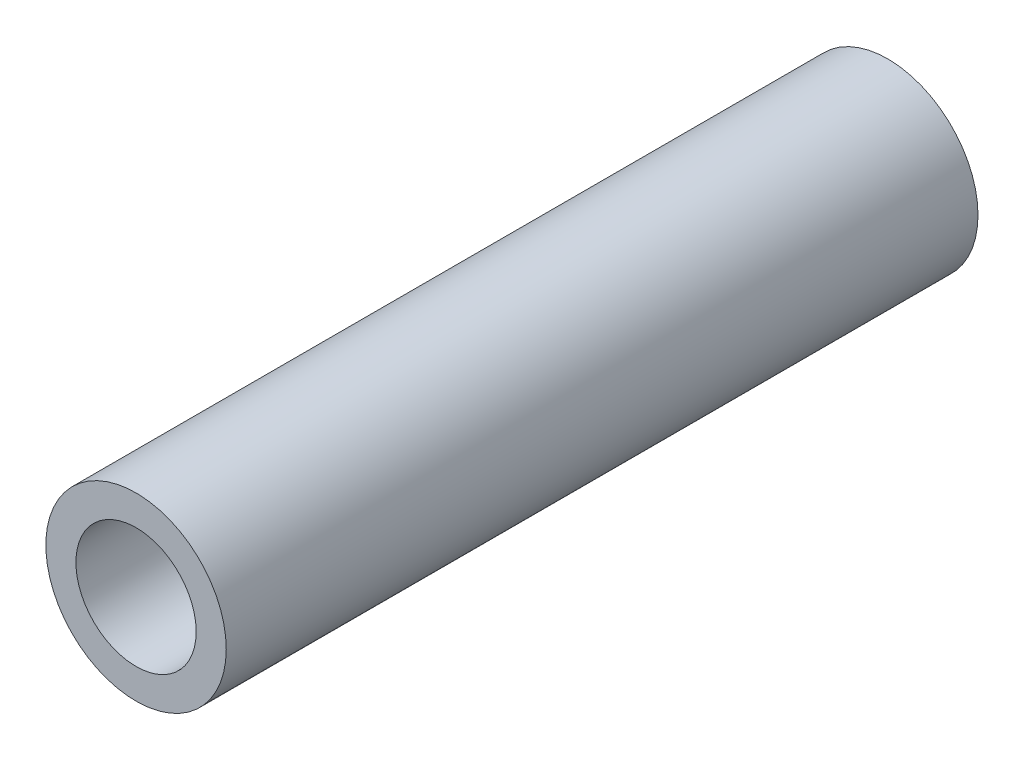
SolidWorks part; units mm, degrees
ref_plane "前视基准面" through (0, 0, 0) normal (0, 0, 1) x (1, 0, 0)
ref_plane "上视基准面" through (0, 0, 0) normal (0, 1, 0) x (1, 0, 0)
ref_plane "右视基准面" through (0, 0, 0) normal (1, 0, 0) x (0, 0, -1)
sketch "草图1" plane through (0, 0, 0) normal (0, 0, 1) x (1, 0, 0)
  circle A0 centre (0, 0) radius 3
  circle A1 centre (0, 0) radius 2
  dimension "D1" = 4
  dimension "D2" = 6
extrude "凸台-拉伸1" add sketch "草图1" along normal mid plane 25
